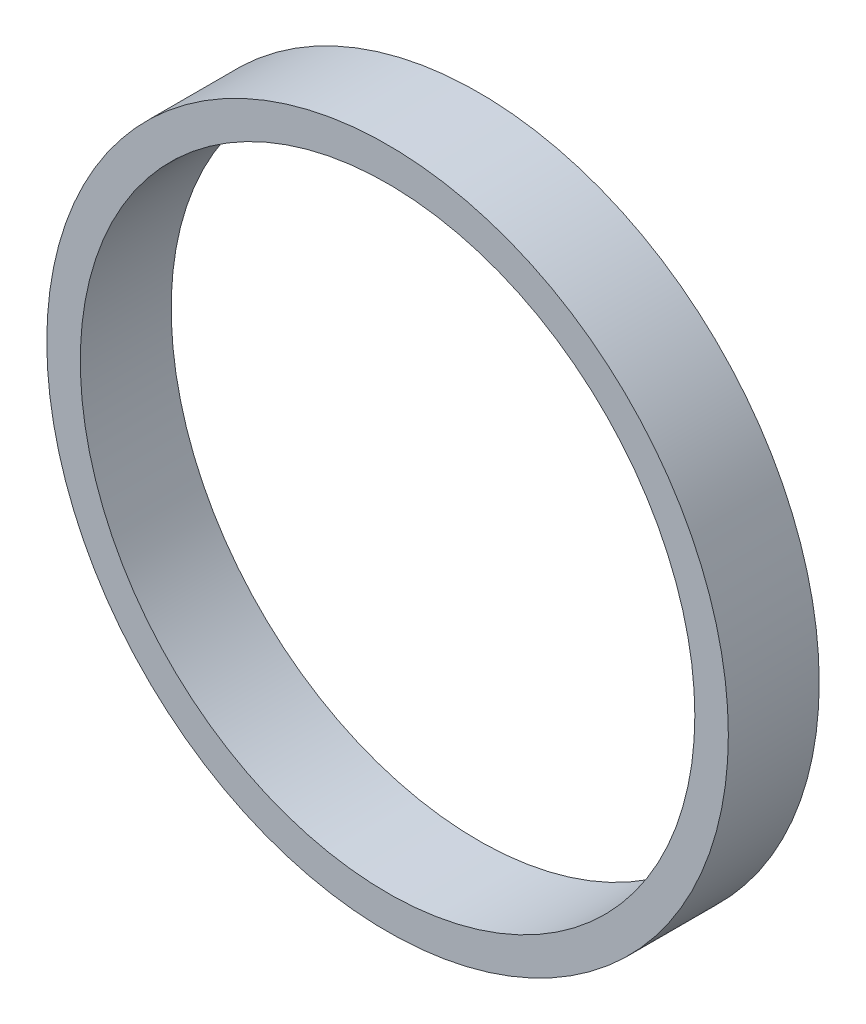
SolidWorks part; units mm, degrees
ref_plane "Front Plane" through (0, 0, 0) normal (1, 0, 0) x (0, 1, 0)
ref_plane "Top Plane" through (0, 0, 0) normal (0, 0, 1) x (0, 1, 0)
ref_plane "Right Plane" through (0, 0, 0) normal (0, 1, 0) x (-1, 0, 0)
sketch "Sketch1" plane through (0, 0, 0) normal (0, 0, 1) x (0, 1, 0)
  circle A0 centre (0, 0) radius 15
  dimension "D1" = 30
extrude "Boss-Extrude1" add sketch "Sketch1" along normal blind 4 contours A0
sketch "Sketch2" plane through (0, 0, 4) normal (0, 0, 1) x (1, 0, 0)
  circle A0 centre (0, 0) radius 13.525
  dimension "D1" = 27.05
extrude "Cut-Extrude1" cut sketch "Sketch2" against normal blind 4
